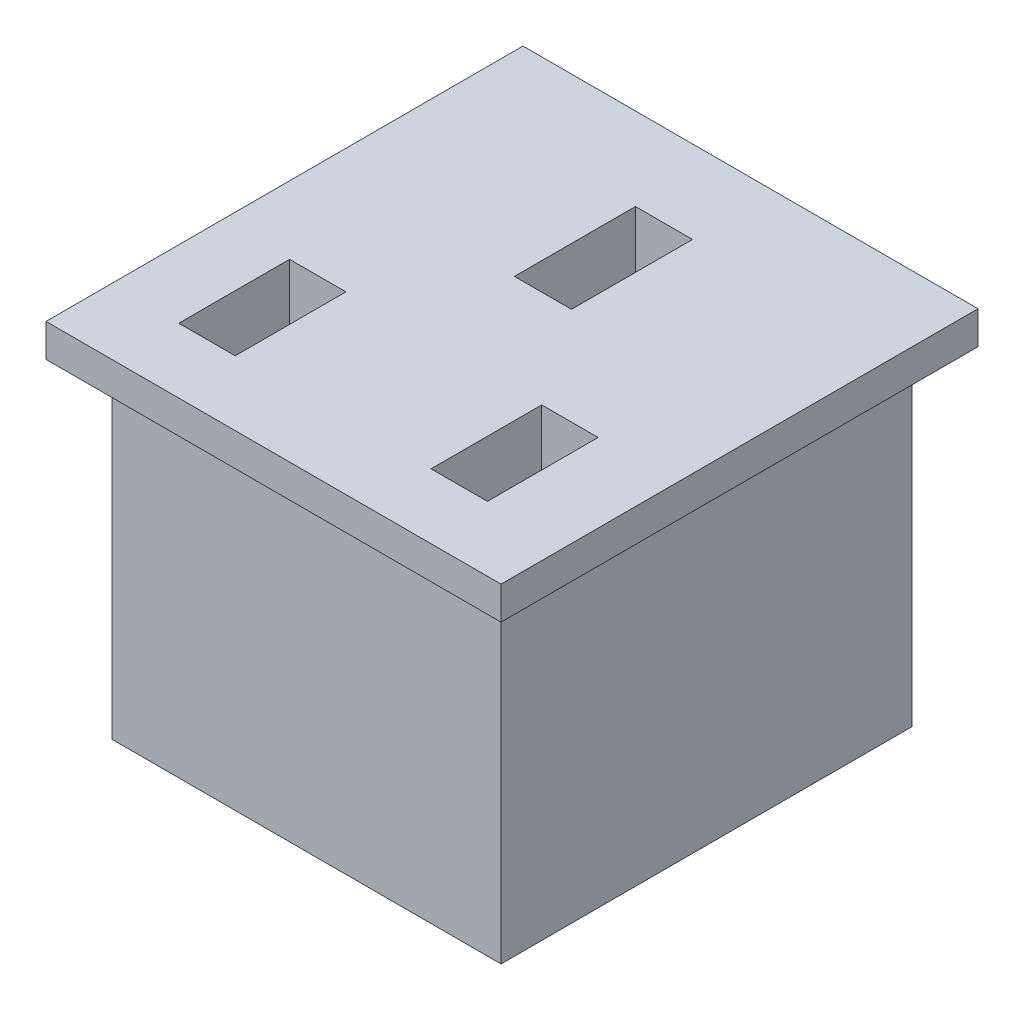
SolidWorks part; units mm, degrees
ref_plane "前视基准面" through (0, 0, 0) normal (0, 0, 1) x (1, 0, 0)
ref_plane "上视基准面" through (0, 0, 0) normal (0, 1, 0) x (1, 0, 0)
ref_plane "右视基准面" through (0, 0, 0) normal (1, 0, 0) x (0, 0, -1)
sketch "草图1" plane through (0, 0, 0) normal (0, 1, 0) x (1, 0, 0)
  line L1 (-17.75, 18.75) -> (17.75, 18.75)
  line L2 (-17.75, 18.75) -> (-17.75, -18.75)
  line L3 (-17.75, -18.75) -> (17.75, -18.75)
  line L4 (17.75, 18.75) -> (17.75, -18.75)
  line L5 (-17.75, 18.75) -> (17.75, -18.75) construction
  line L6 (-17.75, -18.75) -> (17.75, 18.75) construction
  point P0 (0, 0)
  dimension "D1" = 35.5
  dimension "D2" = 37.5
extrude "凸台-拉伸1" add sketch "草图1" along normal blind 30
sketch "草图2" plane through (0, 30, 0) normal (0, 1, 0) x (1, 0, 0)
  line L1 (-20.75, 21.75) -> (20.75, 21.75)
  line L2 (-20.75, 21.75) -> (-20.75, -21.75)
  line L3 (-20.75, -21.75) -> (20.75, -21.75)
  line L4 (20.75, 21.75) -> (20.75, -21.75)
  line L5 (-20.75, 21.75) -> (20.75, -21.75) construction
  line L6 (-20.75, -21.75) -> (20.75, 21.75) construction
  point P0 (0, 0)
  dimension "D1" = 41.5
  dimension "D2" = 43.5
extrude "凸台-拉伸2" add sketch "草图2" along normal blind 3
sketch "草图4" plane through (0, 33, 0) normal (0, 1, 0) x (1, 0, 0)
  line L0 (8.45, -5.7385) -> (8.45, -15.8356)
  line L1 (-2.9476, 14.205) -> (2.2578, 14.205)
  line L2 (-2.9476, 14.205) -> (-2.9476, 3.1671)
  line L3 (-2.9476, 3.1671) -> (2.2578, 3.1671)
  line L4 (2.2578, 14.205) -> (2.2578, 3.1671)
  line L5 (-14.55, -5.7385) -> (-9.4073, -5.7385)
  line L6 (-14.55, -5.7385) -> (-14.55, -15.8356)
  line L7 (-14.55, -15.8356) -> (-9.4073, -15.8356)
  line L8 (-9.4073, -5.7385) -> (-9.4073, -15.8356)
  line L9 (8.45, -5.7385) -> (13.5927, -5.7385)
  line L10 (13.5927, -5.7385) -> (13.5927, -15.8356)
  line L11 (8.45, -15.8356) -> (13.5927, -15.8356)
  dimension "D1" = 2
extrude "切除-拉伸1" cut sketch "草图4" against normal blind 25
